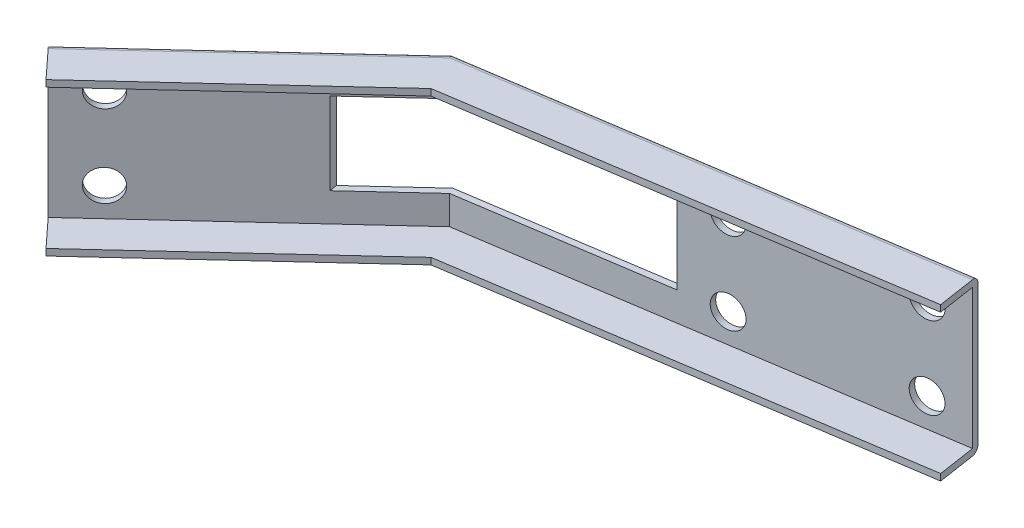
SolidWorks part; units mm, degrees
material "AISI 1020"
ref_plane "Front Plane" through (0, 0, 0) normal (0, 0, 1) x (1, 0, 0)
ref_plane "Top Plane" through (0, 0, 0) normal (0, 1, 0) x (1, 0, 0)
ref_plane "Right Plane" through (0, 0, 0) normal (1, 0, 0) x (0, 0, -1)
sketch "Sketch1" plane through (0, 0, 0) normal (0, 1, 0) x (1, 0, 0)
  line L0 (83.4572, 20.6061) -> (-1.8162, 7.555)
  line L1 (-40.717, -28.3435) -> (-1.8162, 7.555)
  line L2 (-40.717, -28.3435) -> (-41.5647, -27.4249)
  line L3 (-41.5647, -27.4249) -> (-2.3831, 8.7328)
  line L4 (83.4572, 20.6061) -> (83.2681, 21.8417)
  line L5 (83.2681, 21.8417) -> (-2.3831, 8.7328)
extrude "Boss-Extrude1" add sketch "Sketch1" along normal blind 26.64
sketch "Sketch2" plane through (0, 26.64, 0) normal (0, 1, 0) x (1, 0, 0)
  line L0 (83.2681, 21.8417) -> (84.554, 13.4395)
  line L1 (84.554, 13.4395) -> (1.4716, 0.7238)
  line L2 (83.2681, 21.8417) -> (-2.3831, 8.7328)
  line L3 (-2.3831, 8.7328) -> (-41.5647, -27.4249)
  line L4 (-41.5647, -27.4249) -> (-35.8002, -33.6715)
  line L5 (-35.8002, -33.6715) -> (1.4716, 0.7238)
extrude "Boss-Extrude2" add sketch "Sketch2" along normal blind 1.25
sketch "Sketch3" plane through (0, 0, 0) normal (0, -1, 0) x (1, 0, 0)
  line L0 (83.2681, -21.8417) -> (84.554, -13.4395)
  line L1 (84.554, -13.4395) -> (1.4716, -0.7238)
  line L2 (1.4716, -0.7238) -> (-35.8002, 33.6715)
  line L3 (-35.8002, 33.6715) -> (-41.5647, 27.4249)
  line L4 (-41.5647, 27.4249) -> (-2.3831, -8.7328)
  line L5 (-2.3831, -8.7328) -> (83.2681, -21.8417)
extrude "Boss-Extrude3" add sketch "Sketch3" along normal blind 1.25
fillet "Fillet1" radius 1.25 4 edges at (40.4425, -1.25, -15.2872) (-21.9739, -1.25, 9.346) (40.4425, 27.89, -15.2872) (-21.9739, 27.89, 9.346)
sketch "Sketch4" plane through (-1.3605, 0, -8.8893) normal (-0.1513, 0, -0.9885) x (-0.9885, 0, 0.1513)
  line L0 (-85.614, 26.64) -> (-79.264, 26.64) construction
  line L1 (1.0345, 26.64) -> (-85.614, 26.64) construction
  line L2 (-79.264, 26.64) -> (-79.264, 21.14) construction
  line L3 (-79.264, 21.14) -> (-45.964, 21.14) construction
  line L4 (-85.614, 0) -> (-79.264, 0) construction
  line L5 (-85.614, 0) -> (1.0345, 0) construction
  line L6 (-79.264, 0) -> (-79.264, 5.5) construction
  line L7 (-79.264, 5.5) -> (-45.964, 5.5) construction
  circle A0 centre (-79.264, 21.14) radius 3
  circle A1 centre (-45.964, 21.14) radius 3
  circle A2 centre (-45.964, 5.5) radius 3
  circle A3 centre (-79.264, 5.5) radius 3
extrude "Cut-Extrude1" cut sketch "Sketch4" against normal blind 1.25
sketch "Sketch5" plane through (84.6286, 0, -12.9523) normal (0.9885, 0, -0.1513) x (-0.1513, 0, -0.9885)
  line L16 (0.4928, -1.25) -> (7.7428, -1.25)
  line L17 (8.9928, 0) -> (8.9928, 26.64)
  line L18 (7.7428, 27.89) -> (0.4928, 27.89)
  line L19 (0.4928, 27.89) -> (0.4928, 26.64)
  line L20 (0.4928, 26.64) -> (7.7428, 26.64)
  line L21 (7.7428, 26.64) -> (7.7428, 0)
  line L22 (7.7428, 0) -> (0.4928, 0)
  line L23 (0.4928, 0) -> (0.4928, -1.25)
  line L24 (0.4928, -1.25) -> (7.7428, -1.25)
  line L25 (8.9928, 0) -> (8.9928, 26.64)
  line L26 (7.7428, 27.89) -> (0.4928, 27.89)
  line L27 (0.4928, 27.89) -> (0.4928, 26.64)
  line L28 (0.4928, 26.64) -> (7.7428, 26.64)
  line L29 (7.7428, 26.64) -> (7.7428, 0)
  line L30 (7.7428, 0) -> (0.4928, 0)
  line L31 (0.4928, 0) -> (0.4928, -1.25)
  arc A4 (7.7428, -1.25) -> (8.9928, 0) centre (7.7428, 0) ccw
  arc A5 (8.9928, 26.64) -> (7.7428, 27.89) centre (7.7428, 26.64) ccw
  arc A6 (7.7428, -1.25) -> (8.9928, 0) centre (7.7428, 0) ccw
  arc A7 (8.9928, 26.64) -> (7.7428, 27.89) centre (7.7428, 26.64) ccw
  dimension "D1" = 0
extrude "Boss-Extrude4" add sketch "Sketch5" along normal blind 1.25
sketch "Sketch6" plane through (-5.4484, 0, -5.9041) normal (-0.6782, 0, -0.7349) x (-0.7349, 0, 0.6782)
  line L0 (49.1447, 26.64) -> (42.7947, 26.64) construction
  line L1 (49.1447, 26.64) -> (-4.1711, 26.64) construction
  line L2 (42.7947, 26.64) -> (42.7947, 21.14) construction
  line L3 (49.1447, 0) -> (42.7947, 0) construction
  line L4 (-4.1711, 0) -> (49.1447, 0) construction
  line L5 (42.7947, 0) -> (42.7947, 5.5) construction
  circle A0 centre (42.7947, 5.5) radius 3
  circle A1 centre (42.7947, 21.14) radius 3
extrude "Cut-Extrude2" cut sketch "Sketch6" against normal blind 1.25
sketch "Sketch7" plane through (-36.1163, 0, 33.329) normal (-0.7349, 0, 0.6782) x (0.6782, 0, 0.7349)
  line L16 (-8.0339, 26.64) -> (-8.0339, 0)
  line L17 (-6.7839, -1.25) -> (0.4661, -1.25)
  line L18 (0.4661, -1.25) -> (0.4661, 0)
  line L19 (0.4661, 0) -> (-6.7839, 0)
  line L20 (-6.7839, 0) -> (-6.7839, 26.64)
  line L21 (-6.7839, 26.64) -> (0.4661, 26.64)
  line L22 (0.4661, 26.64) -> (0.4661, 27.89)
  line L23 (0.4661, 27.89) -> (-6.7839, 27.89)
  line L24 (-8.0339, 26.64) -> (-8.0339, 0)
  line L25 (-6.7839, -1.25) -> (0.4661, -1.25)
  line L26 (0.4661, -1.25) -> (0.4661, 0)
  line L27 (0.4661, 0) -> (-6.7839, 0)
  line L28 (-6.7839, 0) -> (-6.7839, 26.64)
  line L29 (-6.7839, 26.64) -> (0.4661, 26.64)
  line L30 (0.4661, 26.64) -> (0.4661, 27.89)
  line L31 (0.4661, 27.89) -> (-6.7839, 27.89)
  arc A4 (-8.0339, 0) -> (-6.7839, -1.25) centre (-6.7839, 0) ccw
  arc A5 (-6.7839, 27.89) -> (-8.0339, 26.64) centre (-6.7839, 26.64) ccw
  arc A6 (-8.0339, 0) -> (-6.7839, -1.25) centre (-6.7839, 0) ccw
  arc A7 (-6.7839, 27.89) -> (-8.0339, 26.64) centre (-6.7839, 26.64) ccw
  dimension "D1" = 0
extrude "Boss-Extrude5" add sketch "Sketch7" along normal blind 1.25
sketch "Sketch8" plane through (-1.3605, 0, -8.8893) normal (-0.1513, 0, -0.9885) x (-0.9885, 0, 0.1513)
  line L0 (1.0345, 13.32) -> (-5.9524, 13.32) construction
  line L1 (1.0345, 26.64) -> (1.0345, 0) construction
  line L7 (14.0471, 7.4246) -> (-32.481, 21.14) construction
  line L8 (14.0471, 19.2154) -> (-32.481, 5.5) construction
  line L11 (-37.3938, 21.14) -> (-37.3938, 5.5)
  line L13 (-37.3938, 21.14) -> (14.0471, 21.14)
  line L14 (-37.3938, 5.5) -> (14.0471, 5.5)
  line L15 (14.0471, 21.14) -> (14.0471, 5.5)
extrude "Cut-Extrude3" cut sketch "Sketch8" against normal blind 21.25
